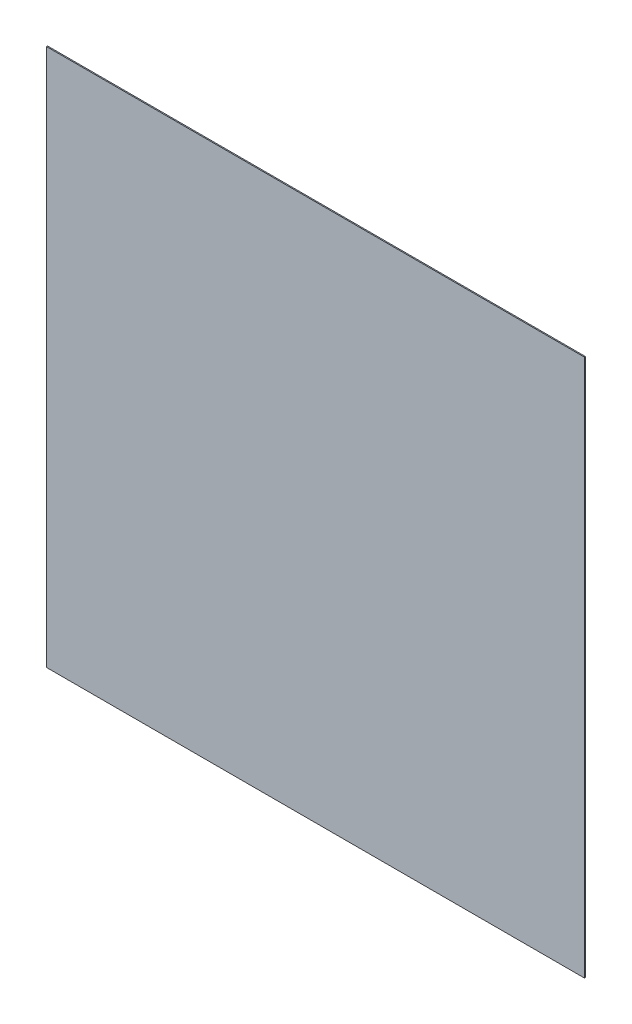
SolidWorks part; units mm, degrees
ref_plane "Front Plane" through (0, 0, 0) normal (0, 0, 1) x (1, 0, 0)
ref_plane "Top Plane" through (0, 0, 0) normal (0, 1, 0) x (1, 0, 0)
ref_plane "Right Plane" through (0, 0, 0) normal (1, 0, 0) x (0, 0, -1)
sketch "Sketch1" plane through (0, 0, 0) normal (0, 0, 1) x (1, 0, 0)
  line L1 (1250, -1250) -> (-1250, -1250)
  line L2 (1250, -1250) -> (1250, 1250)
  line L3 (1250, 1250) -> (-1250, 1250)
  line L4 (-1250, -1250) -> (-1250, 1250)
  line L5 (1250, -1250) -> (-1250, 1250) construction
  line L6 (1250, 1250) -> (-1250, -1250) construction
  point P0 (0, 0)
  dimension "D1" = 2500
  dimension "D2" = 2500
extrude "Boss-Extrude1" add sketch "Sketch1" along normal blind 5
